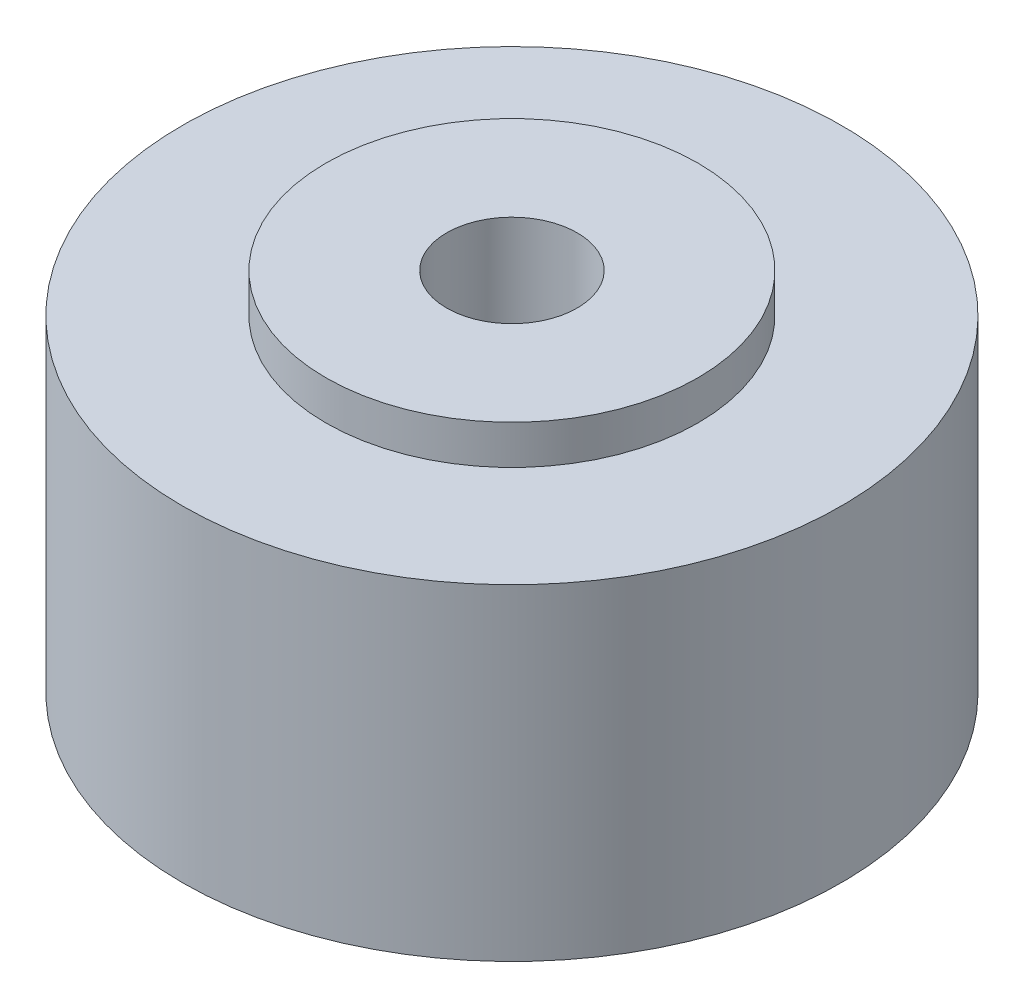
SolidWorks part; units mm, degrees
ref_plane "Front Plane" through (0, 0, 0) normal (0, 0, 1) x (1, 0, 0)
ref_plane "Top Plane" through (0, 0, 0) normal (0, 1, 0) x (1, 0, 0)
ref_plane "Right Plane" through (0, 0, 0) normal (1, 0, 0) x (0, 0, -1)
sketch "Sketch1" plane through (0, 0, 0) normal (0, 0, 1) x (1, 0, 0)
  line L0 (-23.1854, 10) -> (-25.25, 10)
  line L1 (-25.25, 10) -> (-25.25, 35)
  line L2 (-25.25, 35) -> (-14.25, 35)
  line L3 (-5, 38) -> (-5, 24.75)
  line L5 (-14.25, 35) -> (-14.25, 38)
  line L6 (-14.25, 38) -> (-5, 38)
  line L7 (0, 108.1062) -> (0, -62.7915) construction
  arc A0 (-5, 24.75) -> (-23.1854, 10) centre (0, 0) ccw
  dimension "D1" = 50.5
  dimension "D2" = 5
  dimension "D3" = 10
  dimension "D4" = 35
  dimension "D5" = 25.25
  dimension "D6" = 3
  dimension "D7" = 11
revolve "Revolve1" add sketch "Sketch1" angle 360 about L7
